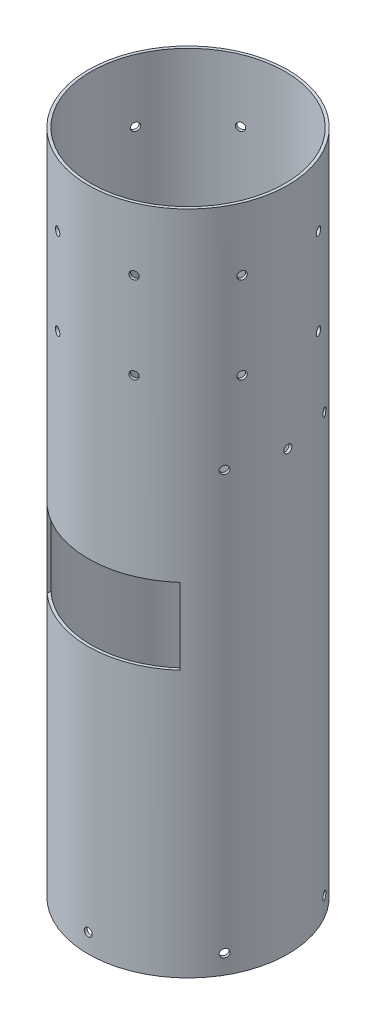
SolidWorks part; units mm, degrees
ref_plane "Спереди" through (0, 0, 0) normal (0, 0, 1) x (1, 0, 0)
ref_plane "Сверху" through (0, 0, 0) normal (0, 1, 0) x (1, 0, 0)
ref_plane "Справа" through (0, 0, 0) normal (1, 0, 0) x (0, 0, -1)
sketch "Эскиз1" plane through (0, 0, 0) normal (0, 0, 1) x (1, 0, 0)
  line L0 (0, 0) -> (0, 131.5742) construction
  line L1 (52.5, 350) -> (52.5, 0)
  line L2 (52.5, 0) -> (51, 0)
  line L3 (51, 0) -> (51, 350)
  line L4 (51, 350) -> (52.5, 350)
  dimension "D1" = 1.5
  dimension "D2" = 102
  dimension "D3" = 350
revolve "Повернуть1" add sketch "Эскиз1" angle 360 about L0
sketch "Эскиз2" plane through (0, 0, 0) normal (0, 0, 1) x (1, 0, 0)
  circle A0 centre (0, 10) radius 2.1
  dimension "D1" = 4.2
  dimension "D2" = 10
extrude "Вырез-Вытянуть2" cut sketch "Эскиз2" against normal blind 88 contours A0
pattern_circular "Круговой массив2" count 6 over 360 about axis through (0, 0, 0) along (0, -1, 0) of "Вырез-Вытянуть2"
sketch "Эскиз3" plane through (0, 0, 0) normal (1, 0, 0) x (0, 0, -1)
  line L0 (51, 350) -> (-51, 350) construction
  circle A0 centre (0, 319) radius 2.1
  dimension "D1" = 4.2
  dimension "D2" = 31
sketch "Эскиз5" plane through (0, 0, 0) normal (0, 1, 0) x (1, 0, 0)
  line L0 (0, 0) -> (0, -51) construction
  line L1 (0, 0) -> (36.0624, -36.0624) construction
  line L2 (0, 0) -> (51, 0) construction
  line L4 (0, 0) -> (19.5169, -47.1179) construction
  line L5 (0, -51) -> (19.5169, -47.1179) construction
  line L6 (0, -51) -> (36.0624, -36.0624) construction
  circle A0 centre (0, 0) radius 51 construction
  dimension "D1" = 45
  dimension "D2" = 22.5
ref_plane "Плоскость2" through (9.7584, 0, 49.0589) normal (0.1951, 0, 0.9808) x (0.9808, 0, -0.1951)
sketch "Эскиз7" plane through (9.7584, 0, 49.0589) normal (0.1951, 0, 0.9808) x (0.9808, 0, -0.1951)
  line L0 (0, 350) -> (0, 0) construction
  line L1 (51, 350) -> (-51, 350) construction
  circle A0 centre (0, 314.5) radius 2.2
  circle A1 centre (0, 269) radius 2.1
  dimension "D1" = 4.4
  dimension "D2" = 35.5
  dimension "D3" = 4.2
  dimension "D4" = 45.5
ref_plane "Плоскость3" through (18.0312, 0, 43.5312) normal (0.3827, 0, 0.9239) x (0.9239, 0, -0.3827)
sketch "Эскиз8" plane through (18.0312, 0, 43.5312) normal (0.3827, 0, 0.9239) x (0.9239, 0, -0.3827)
  line L0 (0, 350) -> (0, 0) construction
  line L1 (51, 350) -> (-51, 350) construction
  circle A0 centre (0, 317) radius 2.1
  circle A1 centre (0, 271.5) radius 2.1
  dimension "D1" = 4.2
  dimension "D2" = 33
  dimension "D3" = 4.2
  dimension "D4" = 45.5
extrude "Вырез-Вытянуть3" cut sketch "Эскиз8" along normal blind 32
pattern_circular "Круговой массив3" count 8 over 360 about axis through (0, 0, 0) along (0, -1, 0) of "Вырез-Вытянуть3"
sketch "Эскиз9" plane through (0, 0, 0) normal (1, 0, 0) x (0, 0, -1)
  line L0 (0, 350) -> (0, 230) construction
  line L1 (0, 350) -> (0, 0) construction
  line L2 (51, 350) -> (-51, 350) construction
  line L3 (51, 350) -> (-51, 350)
  circle A0 centre (0, 230) radius 2.1
  dimension "D2" = 4.2
  dimension "D1" = 120
extrude "Вырез-Вытянуть4" cut sketch "Эскиз9" along normal blind 171 contours A0
pattern_circular "Круговой массив4" count 2 every 30 about axis through (0, 0, 0) along (0, -1, 0) of "Вырез-Вытянуть4"
sketch "Эскиз10" plane through (0, 0, 0) normal (0, 0, 1) x (1, 0, 0)
  line L0 (0, -1000) -> (0, 49000) construction
  line L2 (35, 180) -> (-35, 180)
  line L3 (35, 180) -> (35, 140)
  line L4 (35, 140) -> (-35, 140)
  line L5 (-35, 180) -> (-35, 140)
  line L6 (35, 180) -> (-35, 140) construction
  line L7 (35, 140) -> (-35, 180) construction
  point P1 (0, 160)
  point P8 (35, 160)
  dimension "D1" = 40
  dimension "D2" = 140
  dimension "D3" = 70
extrude "Вырез-Вытянуть5" cut sketch "Эскиз10" along normal through all
